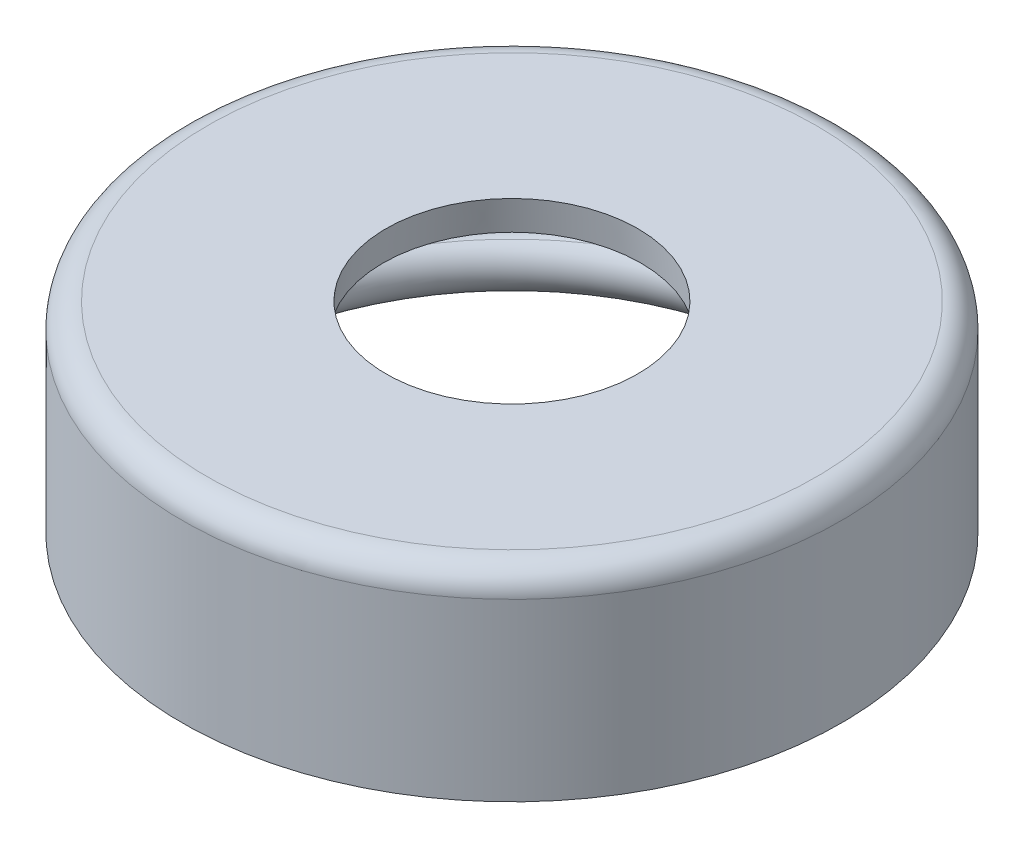
SolidWorks part; units mm, degrees
ref_plane "Front Plane" through (0, 0, 0) normal (0, 0, 1) x (1, 0, 0)
ref_plane "Top Plane" through (0, 0, 0) normal (0, 1, 0) x (1, 0, 0)
ref_plane "Right Plane" through (0, 0, 0) normal (1, 0, 0) x (0, 0, -1)
sketch "Sketch1" plane through (0, 0, 0) normal (0, 0, 1) x (1, 0, 0)
  line L0 (0, 0) -> (0, 14.03)
  line L1 (5.207, 4.9901) -> (5.08, 6.2601)
  line L2 (5.08, 6.2601) -> (12.2809, 6.2601)
  line L3 (13.2969, 5.2441) -> (13.2969, -1.8298)
  line L4 (13.2969, -1.8298) -> (12.0269, -1.8298)
  line L5 (12.0269, 0.5081) -> (12.0269, 4.9901)
  line L6 (12.0269, 4.9901) -> (5.207, 4.9901)
  arc A0 (12.2809, 6.2601) -> (13.2969, 5.2441) centre (12.2809, 5.2441) cw
  arc A1 (11.8024, 0.0866) -> (12.0269, -1.8298) centre (12.4079, -0.8138) ccw
  arc A2 (12.0269, 0.5081) -> (11.8024, 0.0866) centre (11.5189, 0.5081) cw
  dimension "D7" = 1.016
  dimension "D10" = 0.508
  dimension "D1" = 6.8199
  dimension "D2" = 1.27
  dimension "D3" = 0.127
  dimension "D4" = 1.27
  dimension "D5" = 6.8199
  dimension "D6" = 5.08
  dimension "D8" = 1.016
  dimension "D9" = 0.381
revolve "Revolve1" add sketch "Sketch1" angle 360 about L0
